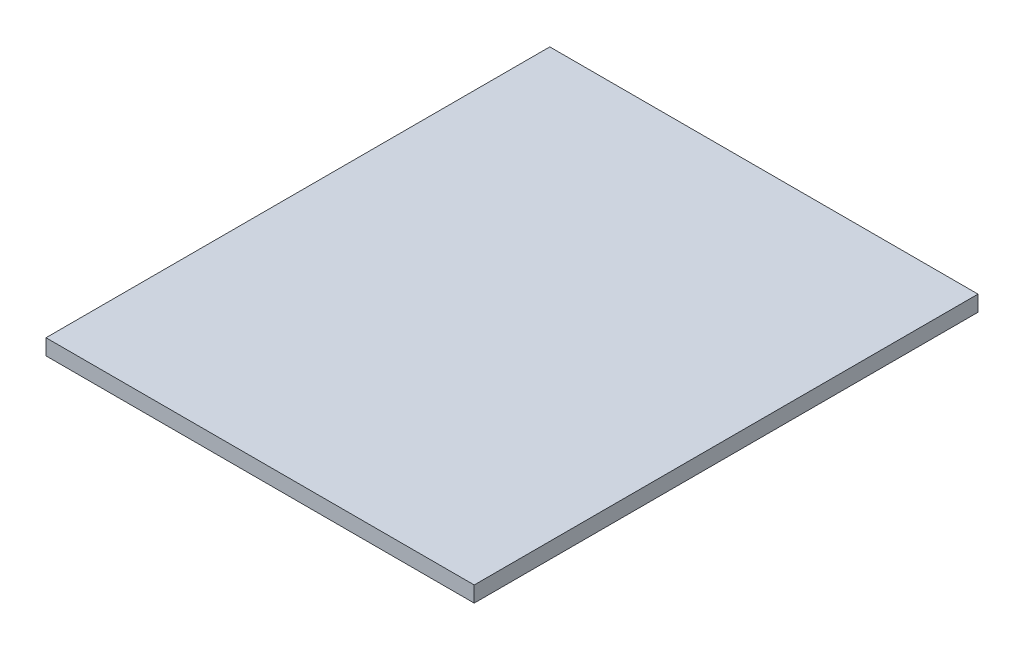
SolidWorks part; units mm, degrees
material "Balsa"
ref_plane "Front Plane" through (0, 0, 0) normal (0, 0, 1) x (1, 0, 0)
ref_plane "Top Plane" through (0, 0, 0) normal (0, 1, 0) x (1, 0, 0)
ref_plane "Right Plane" through (0, 0, 0) normal (1, 0, 0) x (0, 0, -1)
sketch "Sketch1" plane through (0, 0, 0) normal (0, 1, 0) x (1, 0, 0)
  line L1 (-43.18, -50.8) -> (43.18, -50.8)
  line L2 (-43.18, -50.8) -> (-43.18, 50.8)
  line L3 (-43.18, 50.8) -> (43.18, 50.8)
  line L4 (43.18, -50.8) -> (43.18, 50.8)
  line L5 (-43.18, -50.8) -> (43.18, 50.8) construction
  line L6 (-43.18, 50.8) -> (43.18, -50.8) construction
  point P0 (0, 0)
  dimension "D1" = 86.36
  dimension "D2" = 101.6
extrude "Boss-Extrude1" add sketch "Sketch1" along normal blind 3.175
